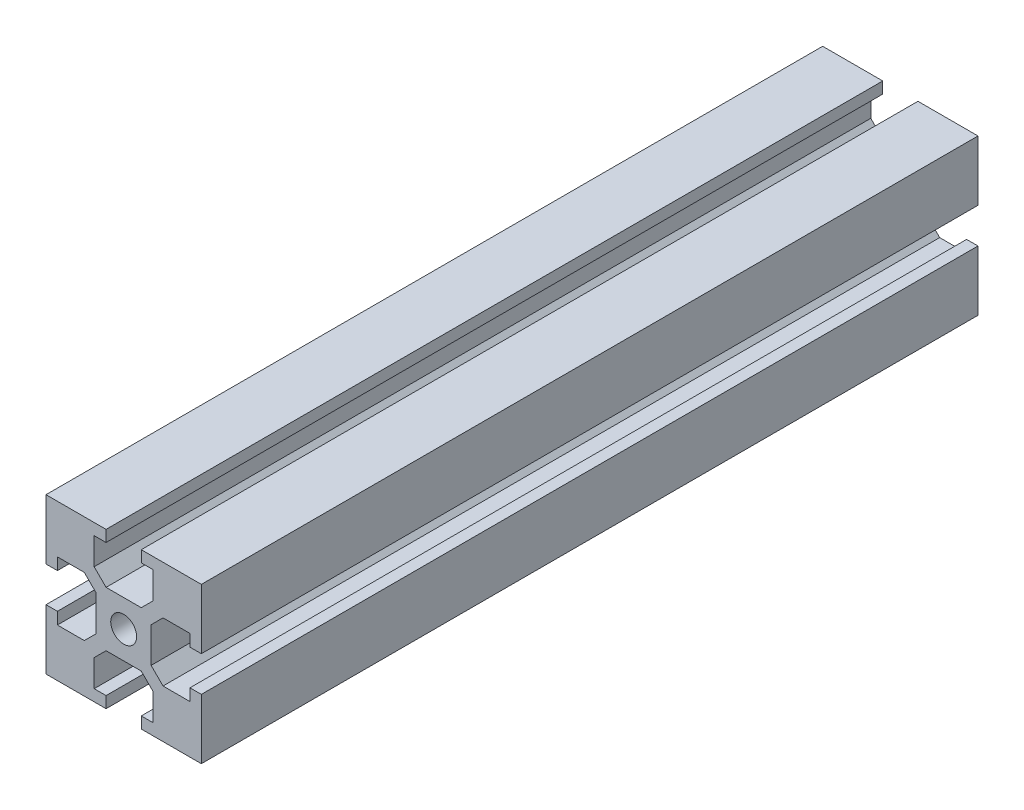
SolidWorks part; units mm, degrees
ref_plane "正面" through (0, 0, 0) normal (0, 0, 1) x (1, 0, 0)
ref_plane "平面" through (0, 0, 0) normal (0, 1, 0) x (1, 0, 0)
ref_plane "右側面" through (0, 0, 0) normal (1, 0, 0) x (0, 0, -1)
sketch "ｽｹｯﾁ2" plane through (0, 0, 0) normal (0, 0, 1) x (1, 0, 0)
  line L0 (0, 0) -> (0, 7.5) construction
  line L1 (-7.5, -7.5) -> (7.5, -7.5) construction
  line L2 (-7.5, -7.5) -> (-7.5, 7.5) construction
  line L3 (-7.5, 7.5) -> (7.5, 7.5) construction
  line L4 (7.5, -7.5) -> (7.5, 7.5) construction
  line L5 (-7.5, -7.5) -> (7.5, 7.5) construction
  line L6 (-7.5, 7.5) -> (7.5, -7.5) construction
  line L8 (1.7, 2.65) -> (-1.7, 2.65)
  line L9 (-2.85, 3.8) -> (2.85, 3.8) construction
  line L10 (-2.85, 6.4) -> (-2.85, 3.8)
  line L11 (2.85, 6.4) -> (2.85, 3.8)
  line L12 (-2.85, 3.8) -> (-1.7, 2.65)
  line L13 (1.7, 2.65) -> (2.85, 3.8)
  line L14 (-2.85, 6.4) -> (-1.7, 6.4)
  line L15 (-1.7, 6.4) -> (-1.7, 7.5)
  line L16 (-1.7, 7.5) -> (-7.5, 7.5)
  line L17 (2.85, 6.4) -> (1.7, 6.4)
  line L18 (1.7, 6.4) -> (1.7, 7.5)
  line L19 (1.7, 7.5) -> (7.5, 7.5)
  line L20 (3.8, 2.85) -> (2.65, 1.7)
  line L21 (2.65, -1.7) -> (2.65, 1.7)
  line L22 (2.65, -1.7) -> (3.8, -2.85)
  line L23 (6.4, -2.85) -> (6.4, -1.7)
  line L24 (6.4, -2.85) -> (3.8, -2.85)
  line L25 (6.4, -1.7) -> (7.5, -1.7)
  line L26 (7.5, -1.7) -> (7.5, -7.5)
  line L27 (6.4, 1.7) -> (7.5, 1.7)
  line L28 (7.5, 1.7) -> (7.5, 7.5)
  line L29 (6.4, 2.85) -> (6.4, 1.7)
  line L30 (6.4, 2.85) -> (3.8, 2.85)
  line L31 (2.85, -3.8) -> (1.7, -2.65)
  line L32 (-1.7, -2.65) -> (1.7, -2.65)
  line L33 (-1.7, -2.65) -> (-2.85, -3.8)
  line L34 (-2.85, -6.4) -> (-1.7, -6.4)
  line L35 (-2.85, -6.4) -> (-2.85, -3.8)
  line L36 (-1.7, -6.4) -> (-1.7, -7.5)
  line L37 (-1.7, -7.5) -> (-7.5, -7.5)
  line L38 (1.7, -6.4) -> (1.7, -7.5)
  line L39 (1.7, -7.5) -> (7.5, -7.5)
  line L40 (2.85, -6.4) -> (1.7, -6.4)
  line L41 (2.85, -6.4) -> (2.85, -3.8)
  line L42 (-3.8, -2.85) -> (-2.65, -1.7)
  line L43 (-2.65, 1.7) -> (-2.65, -1.7)
  line L44 (-2.65, 1.7) -> (-3.8, 2.85)
  line L45 (-6.4, 2.85) -> (-6.4, 1.7)
  line L46 (-6.4, 2.85) -> (-3.8, 2.85)
  line L47 (-6.4, 1.7) -> (-7.5, 1.7)
  line L48 (-7.5, 1.7) -> (-7.5, 7.5)
  line L49 (-6.4, -1.7) -> (-7.5, -1.7)
  line L50 (-7.5, -1.7) -> (-7.5, -7.5)
  line L51 (-6.4, -2.85) -> (-6.4, -1.7)
  line L52 (-6.4, -2.85) -> (-3.8, -2.85)
  circle A0 centre (0, 0) radius 1.25
  point P0 (0, 0)
  point P11 (0, 7.5)
  point P14 (0, 2.65)
  point P17 (0, 3.8)
  dimension "D8" = 2.5
  dimension "D1" = 15
  dimension "D2" = 3.4
  dimension "D3" = 1.1
  dimension "D4" = 2.6
  dimension "D5" = 5.7
  dimension "D6" = 3.4
  dimension "D7" = 4
extrude "ﾎﾞｽ - 押し出し1" add sketch "ｽｹｯﾁ2" along normal blind 75
